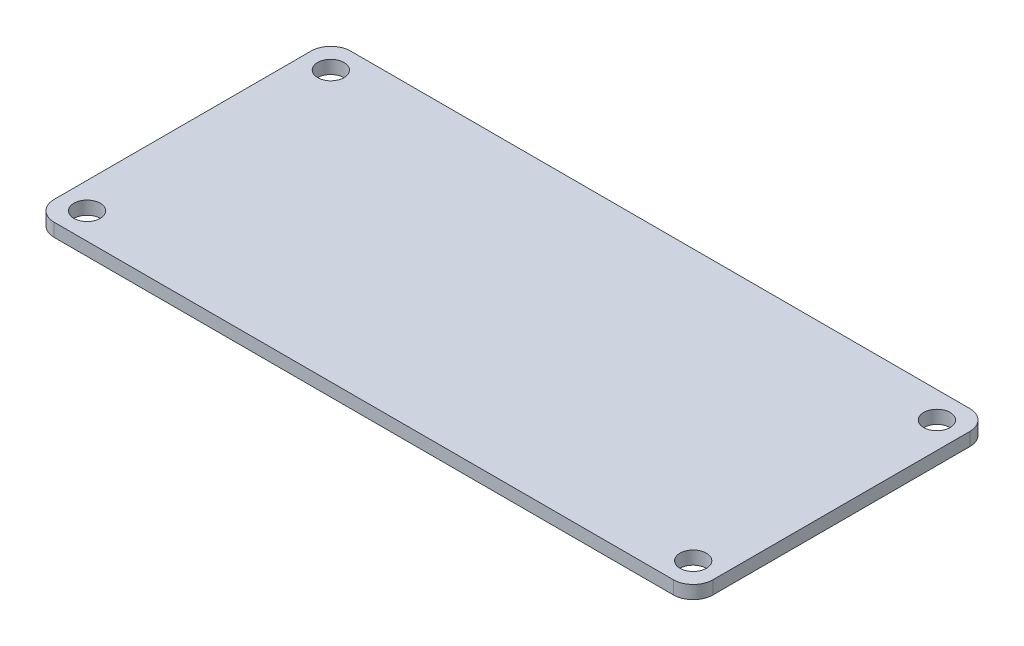
SolidWorks part; units mm, degrees
ref_plane "Plano frontal" through (0, 0, 0) normal (0, 0, 1) x (1, 0, 0)
ref_plane "Plano superior" through (0, 0, 0) normal (0, 1, 0) x (1, 0, 0)
ref_plane "Plano direito" through (0, 0, 0) normal (1, 0, 0) x (0, 0, -1)
sketch "Esboço1" plane through (0, 0, 0) normal (0, 1, 0) x (1, 0, 0)
  line L7 (-50, 22.5) -> (50, 22.5)
  line L8 (50, 22.5) -> (50, -22.5)
  line L9 (50, -22.5) -> (-50, -22.5)
  line L10 (-50, -22.5) -> (-50, 22.5)
  line L11 (0, 22.5) -> (0, -22.5) construction
  line L12 (-50, 0) -> (50, 0) construction
  dimension "D1" = 45
  dimension "D2" = 100
extrude "Ressalto-extrusão1" add sketch "Esboço1" along normal blind 2
sketch "Esboço5" plane through (0, 2, 0) normal (0, 1, 0) x (1, 0, 0)
  line L2 (50, 22.5) -> (-50, 22.5) construction
  line L3 (50, -22.5) -> (50, 22.5) construction
  line L4 (50, 0) -> (-50, 0) construction
  line L5 (-50, 22.5) -> (-50, -22.5) construction
  line L6 (0, 22.5) -> (0, -22.5) construction
  line L7 (-50, -22.5) -> (50, -22.5) construction
  line L8 (53.5484, -13.175) -> (53.5484, -27.5) construction
  line L9 (-53.5484, -13.175) -> (-53.5484, -27.5) construction
  line L10 (-53.5484, 21.175) -> (-53.5484, 35.5) construction
  circle A0 centre (46, 18.5) radius 2
  circle A1 centre (46, -18.5) radius 2
  circle A2 centre (-46, -18.5) radius 2
  circle A3 centre (-46, 18.5) radius 2
  dimension "D2" = 4
  dimension "D1" = 4
  dimension "D3" = 4
extrude "Corte-extrusão3" cut sketch "Esboço5" against normal through all
fillet "Filete1" radius 3 4 edges at (50, 1, -22.5) (50, 1, 22.5) (-50, 1, 22.5) (-50, 1, -22.5)
